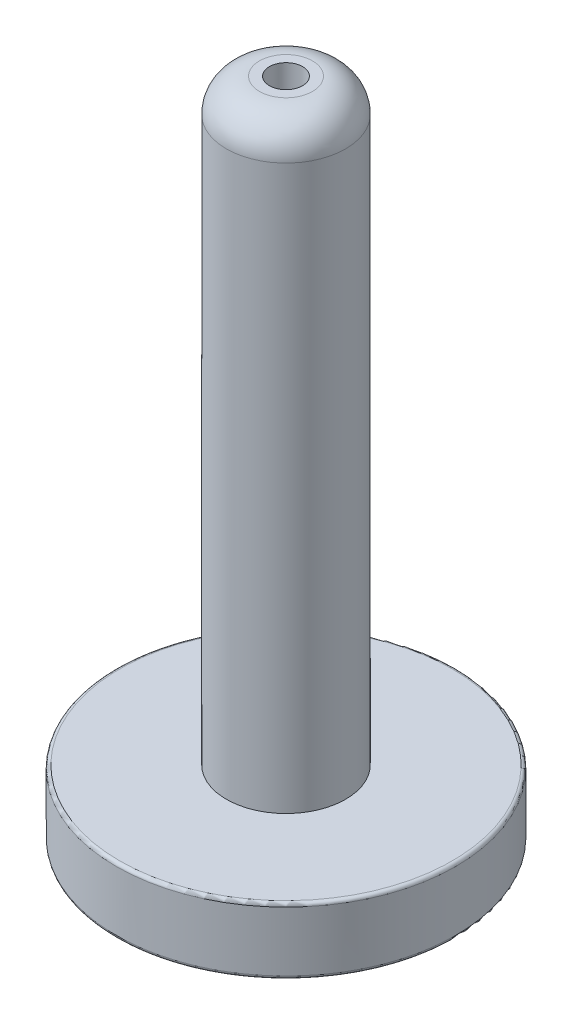
SolidWorks part; units mm, degrees
material "Delrin 2700 NC010, Low Viscosity Acetal Copolymer (SS)"
ref_plane "Front Plane" through (0, 0, 0) normal (0, 0, 1) x (1, 0, 0)
ref_plane "Top Plane" through (0, 0, 0) normal (0, 1, 0) x (1, 0, 0)
ref_plane "Right Plane" through (0, 0, 0) normal (1, 0, 0) x (0, 0, -1)
sketch "Sketch3" plane through (0, 0, 0) normal (0, 0, 1) x (1, 0, 0)
  line L0 (0, 0) -> (0, 127) construction
  line L1 (0, 127) -> (3.175, 127) construction
  line L2 (0, 0) -> (3.175, 0) construction
  line L3 (3.175, 0) -> (9.525, 0) construction
  line L4 (3.175, 0) -> (3.175, 10.9985) construction
  line L5 (3.175, 127) -> (3.175, 10.9985)
  line L6 (3.175, 10.9985) -> (9.525, 0)
  line L7 (9.525, 0) -> (32.5, 0)
  line L8 (32.5, 0) -> (32.5, 12.7)
  line L9 (32.5, 12.7) -> (11.43, 12.7)
  line L10 (11.43, 12.7) -> (11.43, 127)
  line L11 (11.43, 127) -> (3.175, 127)
  dimension "D7" = 11.43
  dimension "D1" = 127
  dimension "D2" = 3.175
  dimension "D3" = 12.7
  dimension "D4" = 32.5
  dimension "D5" = 6.35
  dimension "D6" = 60
revolve "Revolve1" add sketch "Sketch3" angle 360 about L0
fillet "Fillet1" radius 6.35 1 edges at (0, 127, -11.43)
fillet "Fillet2" radius 0.635 2 edges at (0, 12.7, -32.5) (0, 0, -32.5)
fillet "Fillet3" radius 2.54 1 edges at (0, 10.9985, -3.175)
